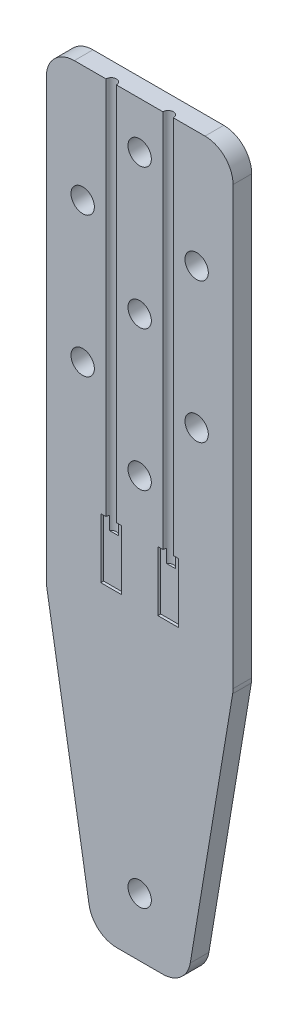
SolidWorks part; units mm, degrees
ref_plane "Front Plane" through (0, 0, 0) normal (0, 0, 1) x (1, 0, 0)
ref_plane "Top Plane" through (0, 0, 0) normal (0, 1, 0) x (1, 0, 0)
ref_plane "Right Plane" through (0, 0, 0) normal (1, 0, 0) x (0, 0, -1)
sketch "Sketch1" plane through (0, 0, 0) normal (0, 0, 1) x (1, 0, 0)
  line L0 (114.3, 63.5) -> (107.95, 25.4) construction
  line L1 (88.9, 63.5) -> (95.25, 25.4) construction
  line L2 (104.713, 67.31) -> (104.713, 158.75) construction
  line L3 (106.237, 67.31) -> (104.713, 67.31) construction
  line L4 (106.237, 158.75) -> (106.237, 67.31) construction
  line L5 (104.713, 158.75) -> (106.237, 158.75) construction
  line L6 (99.125, 127) -> (111.825, 127) construction
  line L7 (104.078, 67.31) -> (104.078, 77.47) construction
  line L8 (106.872, 67.31) -> (104.078, 67.31) construction
  line L9 (106.872, 77.47) -> (106.872, 67.31) construction
  line L10 (104.078, 77.47) -> (106.872, 77.47) construction
  line L11 (96.328, 67.31) -> (96.328, 77.47) construction
  line L12 (99.122, 67.31) -> (96.328, 67.31) construction
  line L13 (99.122, 77.47) -> (99.122, 67.31) construction
  line L14 (96.328, 77.47) -> (99.122, 77.47) construction
  line L15 (114.3, 25.4) -> (114.3, 127) construction
  line L16 (88.9, 25.4) -> (114.3, 25.4) construction
  line L17 (88.9, 127) -> (88.9, 25.4) construction
  line L18 (114.3, 127) -> (88.9, 127) construction
  line L19 (109.35, 127) -> (109.35, 25.4) construction
  line L20 (93.85, 127) -> (93.85, 25.4) construction
  line L21 (96.963, 67.31) -> (96.963, 158.75) construction
  line L22 (98.487, 67.31) -> (96.963, 67.31) construction
  line L23 (98.487, 158.75) -> (98.487, 67.31) construction
  line L24 (96.963, 158.75) -> (98.487, 158.75) construction
  line L25 (91.375, 127) -> (104.075, 127) construction
  line L26 (101.6, 127) -> (101.6, 25.4) construction
  line L27 (105.475, 127) -> (97.725, 127) construction
  line L28 (88.9, 127) -> (88.9, 63.5)
  line L29 (88.9, 63.5) -> (95.25, 25.4)
  line L30 (95.25, 25.4) -> (107.95, 25.4)
  line L31 (107.95, 25.4) -> (114.3, 63.5)
  line L32 (114.3, 63.5) -> (114.3, 127)
  line L33 (114.3, 127) -> (88.9, 127)
  circle A0 centre (93.85, 92.075) radius 1.5875 construction
  circle A1 centre (109.35, 92.075) radius 1.5875 construction
  circle A2 centre (93.85, 111.125) radius 1.5875 construction
  circle A3 centre (109.35, 111.125) radius 1.5875 construction
  circle A4 centre (101.6, 82.55) radius 1.5875 construction
  circle A5 centre (101.6, 101.6) radius 1.5875 construction
  circle A6 centre (101.6, 120.65) radius 1.5875 construction
  circle A7 centre (97.725, 127) radius 0.762 construction
  circle A8 centre (105.475, 127) radius 0.762 construction
extrude "Extrude1" add sketch "Sketch1" against normal blind 2.54
sketch "Sketch2" plane through (0, 0, 0) normal (0, 0, 1) x (1, 0, 0)
  circle A0 centre (93.85, 111.125) radius 1.5875
  circle A1 centre (101.6, 120.65) radius 1.5875
  circle A2 centre (109.35, 111.125) radius 1.5875
  circle A3 centre (101.6, 101.6) radius 1.5875
  circle A4 centre (93.85, 92.075) radius 1.5875
  circle A5 centre (109.35, 92.075) radius 1.5875
  circle A6 centre (101.6, 82.55) radius 1.5875
extrude "Cut-Extrude1" cut sketch "Sketch2" against normal up to surface (2.54 mm away) up to face at (101.6, 71.9667, -2.54)
sketch "Sketch3" plane through (0, 0, 0) normal (0, 0, 1) x (1, 0, 0)
  line L1 (96.328, 75.438) -> (99.122, 75.438)
  line L2 (96.328, 75.438) -> (96.328, 67.31)
  line L3 (96.328, 67.31) -> (99.122, 67.31)
  line L4 (99.122, 75.438) -> (99.122, 67.31)
  line L5 (104.078, 75.438) -> (106.872, 75.438)
  line L6 (104.078, 75.438) -> (104.078, 67.31)
  line L7 (104.078, 67.31) -> (106.872, 67.31)
  line L8 (106.872, 75.438) -> (106.872, 67.31)
extrude "Cut-Extrude2" cut sketch "Sketch3" against normal blind 0.381
sketch "Sketch4" plane through (0, 127, 0) normal (0, 1, 0) x (1, 0, 0)
  circle A0 centre (97.725, 0) radius 0.7112
  circle A1 centre (105.475, 0) radius 0.7112
extrude "Cut-Extrude3" cut sketch "Sketch4" against normal blind 53.34
fillet "Fillet1" radius 3.81 6 edges at (114.3, 127, -1.27) (107.95, 25.4, -1.27) (114.3, 63.5, -1.27) (95.25, 25.4, -1.27) (88.9, 63.5, -1.27) (88.9, 127, -1.27)
sketch "Sketch5" plane through (0, 0, 0) normal (0, 0, 1) x (1, 0, 0)
  line L0 (101.6, 25.4) -> (101.6, 33.3375) construction
  line L1 (101.6, 127) -> (101.6, 25.4) construction
  circle A0 centre (101.6, 33.3375) radius 1.5875
extrude "Cut-Extrude4" cut sketch "Sketch5" against normal up to surface (2.54 mm away) up to face at (103.1875, 82.55, -2.54)
